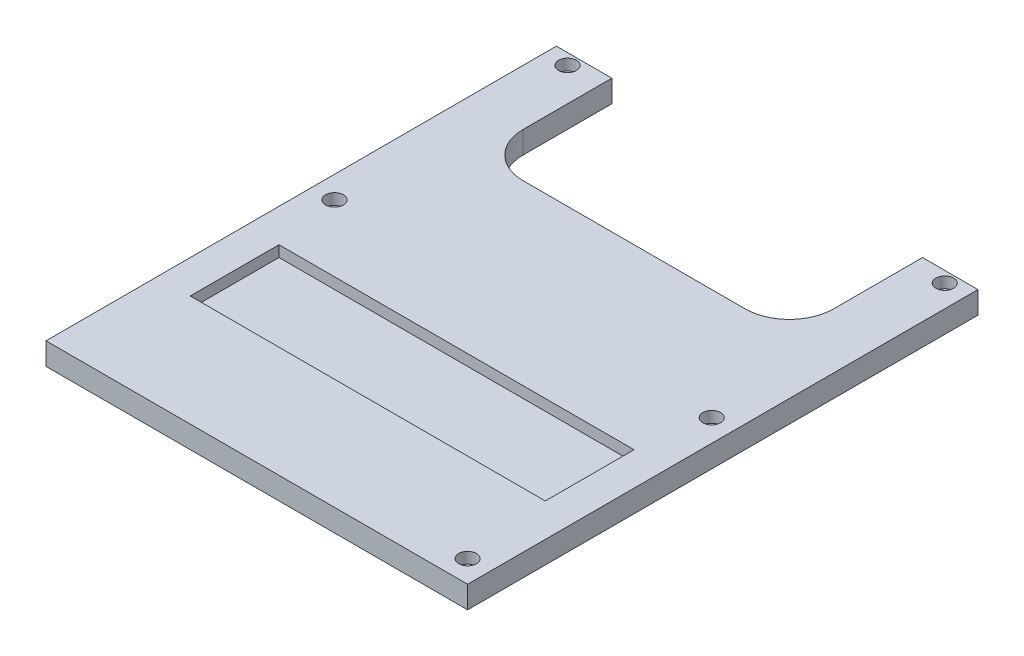
SolidWorks part; units mm, degrees
material "ABS"
ref_plane "Front" through (0, 0, 0) normal (0, 0, 1) x (1, 0, 0)
ref_plane "Top" through (0, 0, 0) normal (0, 1, 0) x (1, 0, 0)
ref_plane "Right" through (0, 0, 0) normal (1, 0, 0) x (0, 0, -1)
sketch "Sketch1" plane through (0, 0, 0) normal (0, 1, 0) x (1, 0, 0)
  line L1 (-60.325, 73.025) -> (60.325, 73.025)
  line L2 (-60.325, 73.025) -> (-60.325, -73.025)
  line L3 (-60.325, -73.025) -> (60.325, -73.025)
  line L4 (60.325, 73.025) -> (60.325, -73.025)
  line L5 (-60.325, 73.025) -> (60.325, -73.025) construction
  line L6 (-60.325, -73.025) -> (60.325, 73.025) construction
  point P0 (0, 0)
  dimension "D1" = 120.65
  dimension "D2" = 146.05
extrude "Boss-Extrude1" add sketch "Sketch1" along normal blind 6.35
sketch "Sketch7" plane through (0, 6.35, 0) normal (0, 1, 0) x (1, 0, 0)
  line L1 (-60.325, 73.025) -> (-60.325, -73.025) construction
  line L2 (60.325, -73.025) -> (60.325, 73.025) construction
  line L3 (-60.325, -73.025) -> (60.325, -73.025) construction
  circle A0 centre (-53.975, 3.175) radius 2.54
  circle A1 centre (53.975, 3.175) radius 2.54
  circle A2 centre (53.975, -66.675) radius 2.54
  circle A3 centre (-53.975, 69.85) radius 2.54
  circle A4 centre (53.975, 69.85) radius 2.54
  point P12 (0, 0)
  point P15 (0, 0)
  point P18 (0, 0)
  dimension "D5" = 5.08
  dimension "D1" = 76.2
  dimension "D2" = 6.35
  dimension "D3" = 6.35
  dimension "D4" = 6.35
  dimension "D6" = 66.675
extrude "Cut-Extrude1" cut sketch "Sketch7" against normal offset from surface (3.175 mm away) 3.175 up to face at (0, 0, 0)
hole_wizard "#2 Clearance Hole2" positions "Sketch8" profile "Sketch10" hole size "#2" standard "ANSI Inch" end condition through all
sketch "Sketch8" plane through (0, 3.175, 0) normal (0, 1, 0) x (1, 0, 0)
  point P0 (-53.975, 3.175)
  point P3 (53.975, 3.175)
  point P6 (53.975, -66.675)
  point P9 (-53.975, 69.85)
  point P12 (53.975, 69.85)
sketch "Sketch10" plane through (-53.975, 3.175, -3.175) normal (1, 0, 0) x (0, 0, 1)
  line L0 (0, 0) -> (0, 3.175)
  line L1 (0, 3.175) -> (1.0795, 3.175)
  line L2 (1.0795, 3.175) -> (1.0795, 0.8275)
  line L3 (1.0795, 0.8275) -> (1.7145, 0)
  line L5 (1.7145, 0) -> (0, 0)
  line L6 (-1.0795, 0.8275) -> (-1.7145, 0) construction
  line L11 (0, -6.35) -> (0, 107.95) construction
  dimension "Thru Hole Dia." = 2.159
  dimension "Thru Hole Depth" = 3.175
  dimension "Near C'Sink Dia." = 3.429
  dimension "Near C'Sink Angle" = 75
sketch "Sketch13" plane through (0, 6.35, 0) normal (0, 1, 0) x (1, 0, 0)
  line L0 (60.325, 73.025) -> (-60.325, 73.025) construction
  line L1 (-44.45, 73.025) -> (44.45, 73.025)
  line L2 (-44.45, 73.025) -> (-44.45, 34.925)
  line L3 (-44.45, 34.925) -> (44.45, 34.925)
  line L4 (44.45, 73.025) -> (44.45, 34.925)
  line L5 (-44.45, 73.025) -> (44.45, 34.925) construction
  line L6 (-44.45, 34.925) -> (44.45, 73.025) construction
  point P0 (0, 53.975)
  point P5 (0, 0)
  point P7 (0, 0)
  dimension "D1" = 88.9
  dimension "D2" = 38.1
extrude "Cut-Extrude3" cut sketch "Sketch13" against normal through all
fillet "Fillet1" radius 12.7 2 edges at (44.45, 3.175, -34.925) (-44.45, 3.175, -34.925)
sketch "Sketch11" plane through (0, 6.35, 0) normal (0, 1, 0) x (1, 0, 0)
  line L0 (-60.325, -73.025) -> (60.325, -73.025) construction
  line L1 (-50.8, -15.875) -> (50.8, -15.875)
  line L2 (-50.8, -15.875) -> (-50.8, -41.275)
  line L3 (-50.8, -41.275) -> (50.8, -41.275)
  line L4 (50.8, -15.875) -> (50.8, -41.275)
  line L5 (-50.8, -15.875) -> (50.8, -41.275) construction
  line L6 (-50.8, -41.275) -> (50.8, -15.875) construction
  point P0 (0, -28.575)
  point P5 (0, 0)
  point P6 (0, 0)
  point P7 (0, 0)
  point P10 (0, 0)
  point P11 (11.7991, 0)
  dimension "D1" = 25.4
  dimension "D2" = 101.6
  dimension "D3" = 44.45
extrude "Cut-Extrude2" cut sketch "Sketch11" against normal blind 3.175
